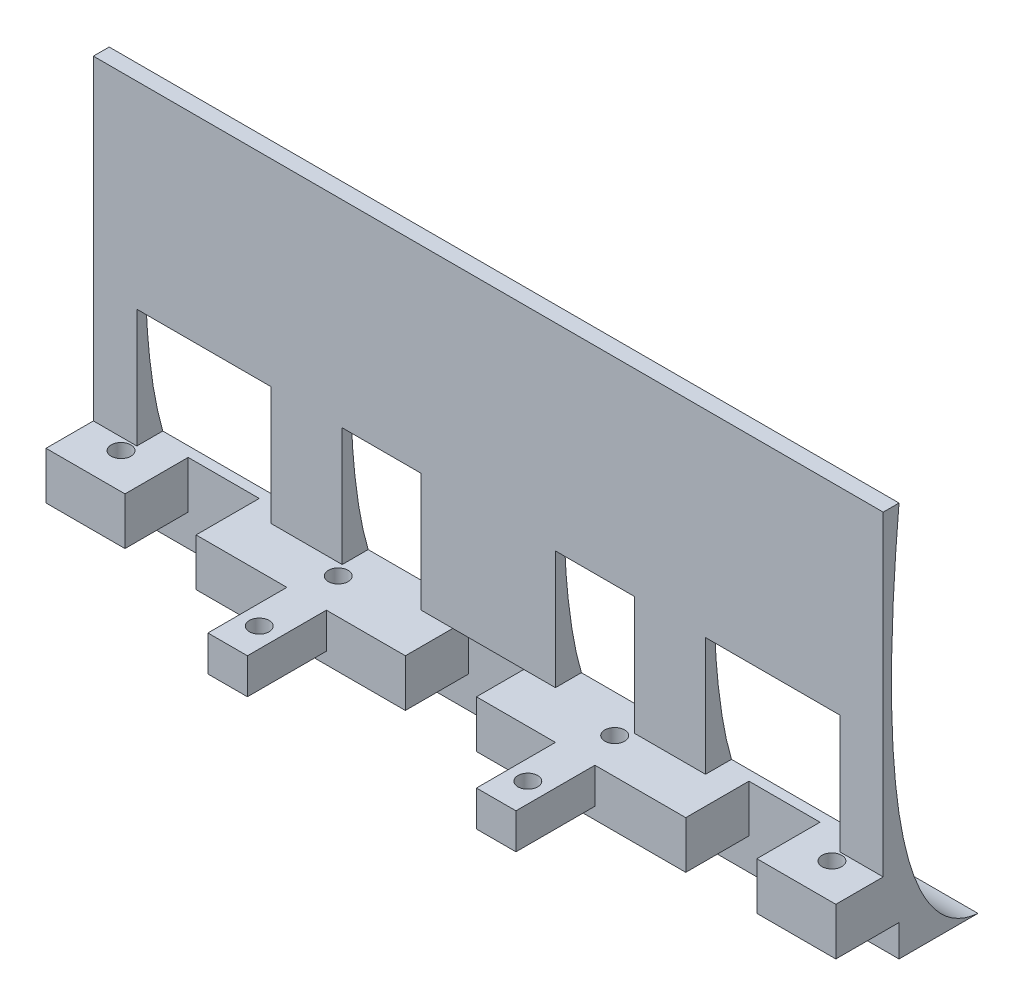
SolidWorks part; units mm, degrees
ref_plane "Płaszczyzna przednia" through (0, 0, 0) normal (0, 0, 1) x (1, 0, 0)
ref_plane "Płaszczyzna górna" through (0, 0, 0) normal (0, 1, 0) x (1, 0, 0)
ref_plane "Płaszczyzna prawa" through (0, 0, 0) normal (1, 0, 0) x (0, 0, -1)
sketch "Szkic1" plane through (0, 0, 0) normal (0, 1, 0) x (1, 0, 0)
  line L0 (0, 0) -> (-100, 0)
  line L1 (-100, 0) -> (-100, 28)
  line L2 (-100, 28) -> (0, 28)
  line L3 (0, 28) -> (0, 0)
  dimension "D1" = 100
  dimension "D2" = 28
extrude "ogolny ksztalt" add sketch "Szkic1" along normal blind 50
sketch "zakrzywuienie" plane through (0, 0, 0) normal (1, 0, 0) x (0, 0, -1)
  line L0 (28, 0) -> (18, 0)
  line L1 (0, 0) -> (28, 0) construction
  line L3 (0, 50) -> (28, 50) construction
  line L4 (18, 0) -> (0, 0)
  line L5 (0, 0) -> (0, 50)
  line L6 (0, 50) -> (18, 50)
  spline S0 degree 3 poles (18, 50) (14.6936, 12.9926) (20.3971, 0.6928) (28, 0) knots 0 0 0 0 1 1 1 1
  dimension "D1" = 10
  dimension "D2" = 18
extrude "wyciecie ksztal przod" cut sketch "zakrzywuienie" against normal blind 105 flip side to cut
sketch "Szkic4" plane through (0, 0, 0) normal (0, -1, 0) x (-1, 0, 0)
  line L0 (69.5, 0) -> (30.5, 0)
  line L1 (100, 0) -> (0, 0) construction
  line L2 (100, 28) -> (100, 0) construction
  line L3 (30.5, 0) -> (30.5, 10)
  line L4 (69.5, 0) -> (69.5, 10)
  line L5 (69.5, 10) -> (100, 10)
  line L6 (100, 10) -> (100, 0)
  line L7 (100, 0) -> (69.5, 0)
  line L8 (30.5, 0) -> (0, 0)
  line L9 (30.5, 10) -> (0, 10)
  line L10 (0, 0) -> (0, 28) construction
  line L11 (0, 10) -> (0, 0)
  line M4 (0, 28) -> (0, 0)
  line M5 (0, 0) -> (100, 0)
  line M6 (100, 0) -> (100, 28)
  dimension "D1" = 39
  dimension "D2" = 30.5
  dimension "D3" = 30.5
  dimension "D4" = 10
  dimension "D5" = 10
extrude "wyciecie ksztaltu tyl" cut sketch "Szkic4" against normal blind 99.5 and the other way blind 23 contours L5 L4 M5 M6 | L3 L9 M4 M5
sketch "Szkic5" plane through (0, 0, 0) normal (0, -1, 0) x (-1, 0, 0)
  line L0 (30.5, 0) -> (69.5, 0)
  line L1 (69.5, 0) -> (69.5, 10)
  line L2 (69.5, 10) -> (30.5, 10)
  line L3 (30.5, 10) -> (30.5, 0)
extrude "podbicie tyl(spod)" cut sketch "Szkic5" against normal blind 5.5
sketch "Szkic6" plane through (0, 0, 0) normal (0, -1, 0) x (-1, 0, 0)
  line L0 (0, 10) -> (100, 10)
  line L1 (100, 10) -> (100, 18)
  line L2 (100, 28) -> (100, 10) construction
  line L3 (100, 18) -> (0, 18)
  line L4 (0, 10) -> (0, 28) construction
  line L5 (0, 18) -> (0, 10)
  dimension "D1" = 8
extrude "podbicie srodek(spod)" cut sketch "Szkic6" against normal blind 4
sketch "Szkic7" plane through (0, 50, 0) normal (0, 1, 0) x (1, 0, 0)
  line L2 (0, 10) -> (-30.5, 10)
  line L3 (-30.5, 10) -> (-30.5, 0)
  line L4 (-30.5, 0) -> (-69.5, 0)
  line L5 (-69.5, 0) -> (-69.5, 10)
  line L6 (-69.5, 10) -> (-100, 10)
  line L8 (-100, 10) -> (-100, 16)
  line L10 (-100, 18) -> (-100, 10) construction
  line L11 (-100, 16) -> (0, 16)
  line L12 (0, 10) -> (0, 18) construction
  line L13 (0, 16) -> (0, 10)
  dimension "D1" = 6
extrude "przyciecie od gory" cut sketch "Szkic7" against normal blind 40
sketch "Szkic8" plane through (0, 5.5, 0) normal (0, -1, 0) x (-1, 0, 0)
  line L0 (0, 28) -> (100, 28) construction
  line L1 (30.5, 10) -> (30.5, 0) construction
  line L2 (69.5, 0) -> (69.5, 10) construction
  line L3 (100, 10) -> (100, 18) construction
  line L4 (0, 18) -> (0, 10) construction
  circle A0 centre (67, 4) radius 1.25
  circle A1 centre (33, 4) radius 1.25
  circle A2 centre (67.5, 14.5) radius 1.25
  circle A3 centre (32.5, 14.5) radius 1.25
  circle A4 centre (95, 14.5) radius 1.25
  circle A5 centre (5, 14.5) radius 1.25
  dimension "D6" = 2.5
  dimension "D7" = 2.5
  dimension "D17" = 2.5
  dimension "D18" = 2.5
  dimension "D19" = 2.5
  dimension "D20" = 2.5
  dimension "D1" = 24
  dimension "D2" = 24
  dimension "D3" = 34
  dimension "D4" = 2.5
  dimension "D5" = 2.5
  dimension "D8" = 13.5
  dimension "D9" = 13.5
  dimension "D10" = 35
  dimension "D11" = 13.5
  dimension "D12" = 13.5
  dimension "D13" = 5
  dimension "D14" = 32.5
  dimension "D15" = 5
  dimension "D16" = 32.5
extrude "otwory na sruby" cut sketch "Szkic8" against normal blind 71 and the other way blind 90
sketch "Szkic9" plane through (0, 0, 0) normal (0, -1, 0) x (-1, 0, 0)
  line L0 (0, 28) -> (100, 28) construction
  line L1 (45.5, 18) -> (54.5, 18)
  line L2 (45.5, 18) -> (45.5, 8)
  line L3 (45.5, 8) -> (54.5, 8)
  line L4 (54.5, 18) -> (54.5, 8)
  line L5 (100, 18) -> (0, 18) construction
  line L6 (10, 18) -> (19, 18)
  line L7 (10, 18) -> (10, 8)
  line L8 (10, 8) -> (19, 8)
  line L9 (19, 18) -> (19, 8)
  line L10 (100, 18) -> (0, 18) construction
  line L11 (90, 18) -> (81, 18)
  line L12 (90, 18) -> (90, 8)
  line L13 (90, 8) -> (81, 8)
  line L14 (81, 18) -> (81, 8)
  line L16 (100, 10) -> (100, 18) construction
  dimension "D1" = 10
  dimension "D2" = 9
  dimension "D3" = 10
  dimension "D4" = 26.5
  dimension "D5" = 26.5
  dimension "D6" = 10
  dimension "D7" = 9
  dimension "D8" = 9
  dimension "D9" = 10
  dimension "D10" = 10
  dimension "D11" = 10
extrude "ktir kable" cut sketch "Szkic9" against normal blind 10
sketch "Szkic10" plane through (0, 5.5, 0) normal (0, -1, 0) x (1, 0, 0)
  line L0 (-35.5, 0) -> (-64.5, 0)
  line L1 (-30.5, 0) -> (-69.5, 0) construction
  line L2 (-64.5, 0) -> (-64.5, -10)
  line L3 (0, -10) -> (-10, -10) construction
  line L4 (-64.5, -10) -> (-35.5, -10)
  line L5 (-69.5, -10) -> (-54.5, -10) construction
  line L6 (-35.5, -10) -> (-35.5, 0)
  line L7 (-30.5, -10) -> (-30.5, 0) construction
  line L8 (-69.5, 0) -> (-69.5, -10) construction
  dimension "D1" = 29
  dimension "D2" = 5
  dimension "D3" = 5
extrude "Wytnij-wyciągnięcie3" cut sketch "Szkic10" against normal blind 81 and the other way blind 84
sketch "Szkic11" plane through (0, 0, -16) normal (0, 0, 1) x (1, 0, 0)
  line L0 (-68.5, 10) -> (-68.5, 25)
  line L1 (-69.5, 10) -> (-64.5, 10) construction
  line L2 (-68.5, 25) -> (-58.5, 25)
  line L3 (-58.5, 25) -> (-58.5, 10)
  line L4 (-45.5, 10) -> (-54.5, 10) construction
  line L5 (-58.5, 10) -> (-68.5, 10)
  line L6 (-69.5, 5.5) -> (-69.5, 10) construction
  line L7 (-31.5, 10) -> (-41.5, 10)
  line L8 (-35.5, 10) -> (-30.5, 10) construction
  line L9 (-35.5, 10) -> (-45.5, 10) construction
  line L10 (-41.5, 10) -> (-41.5, 25)
  line L11 (-41.5, 25) -> (-31.5, 25)
  line L12 (-31.5, 25) -> (-31.5, 10)
  line L13 (-30.5, 10) -> (-30.5, 5.5) construction
  line L14 (-77.5, 10) -> (-77.5, 25)
  line L15 (-81, 10) -> (-69.5, 10) construction
  line L16 (-77.5, 25) -> (-94.5, 25)
  line L17 (-94.5, 25) -> (-94.5, 10)
  line L18 (-90, 10) -> (-81, 10) construction
  line L19 (-94.5, 10) -> (-77.5, 10)
  line L20 (-81, 10) -> (-81, 4) construction
  line L22 (-22.5, 10) -> (-22.5, 25)
  line L23 (-30.5, 10) -> (-19, 10) construction
  line L24 (-22.5, 25) -> (-5.5, 25)
  line L25 (-5.5, 25) -> (-5.5, 10)
  line L26 (-19, 10) -> (-10, 10) construction
  line L27 (-5.5, 10) -> (-22.5, 10)
  line L28 (-19, 4) -> (-19, 10) construction
  dimension "D1" = 1
  dimension "D2" = 10
  dimension "D3" = 15
  dimension "D4" = 1
  dimension "D5" = 10
  dimension "D6" = 15
  dimension "D7" = 17
  dimension "D8" = 8
  dimension "D9" = 3.5
  dimension "D10" = 15
  dimension "D11" = 17
  dimension "D12" = 15
  dimension "D13" = 8
  dimension "D14" = 3.5
extrude "Wytnij-wyciągnięcie4" cut sketch "Szkic11" against normal blind 55 and the other way blind 59
